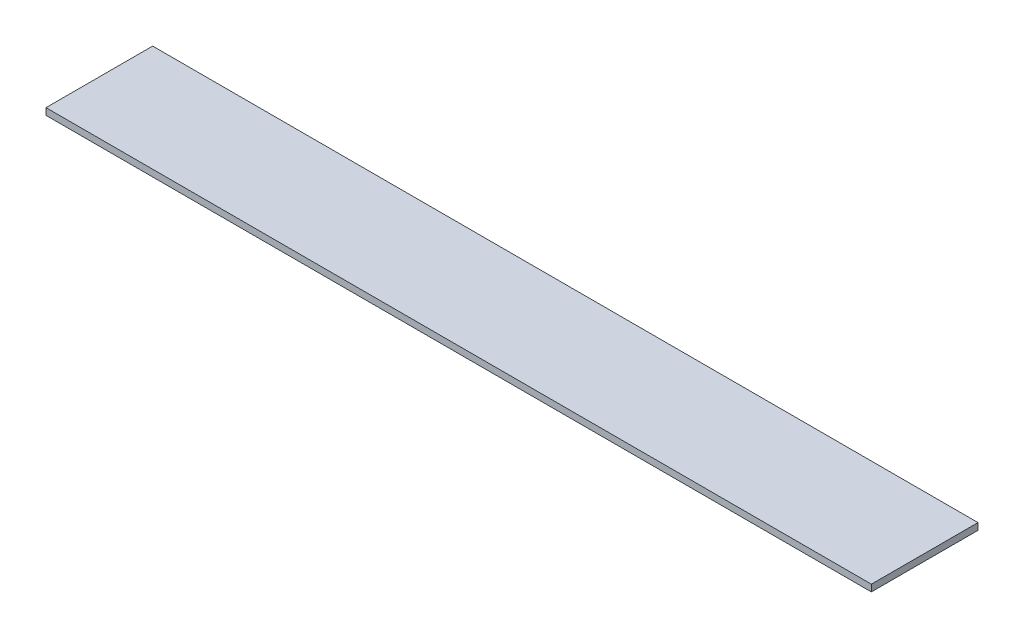
SolidWorks part; units mm, degrees
ref_plane "Front Plane" through (0, 0, 0) normal (0, 0, 1) x (1, 0, 0)
ref_plane "Top Plane" through (0, 0, 0) normal (0, 1, 0) x (1, 0, 0)
ref_plane "Right Plane" through (0, 0, 0) normal (1, 0, 0) x (0, 0, -1)
sketch "Sketch1" plane through (0, 0, 0) normal (0, 1, 0) x (1, 0, 0)
  line L1 (0, 0) -> (311.15, 0)
  line L2 (0, 0) -> (0, 40.2)
  line L3 (0, 40.2) -> (311.15, 40.2)
  line L4 (311.15, 0) -> (311.15, 40.2)
  dimension "D1" = 311.15
  dimension "D2" = 40.2
extrude "Boss-Extrude1" add sketch "Sketch1" along normal blind 2.54
